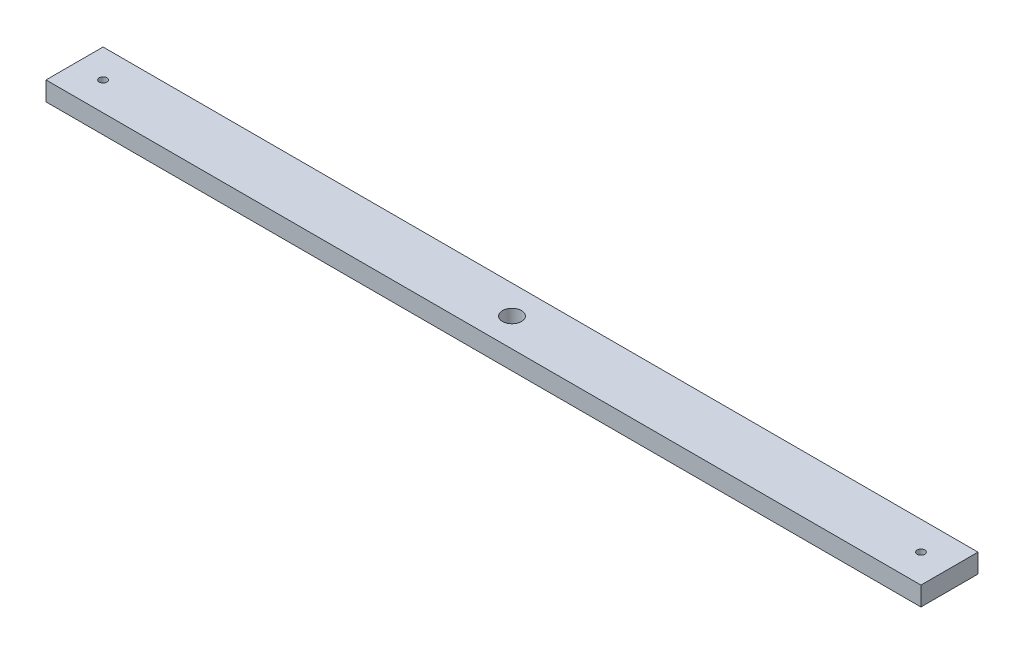
SolidWorks part; units mm, degrees
material "6061 Alloy"
ref_plane "Front Plane" through (0, 0, 0) normal (0, 0, 1) x (1, 0, 0)
ref_plane "Top Plane" through (0, 0, 0) normal (0, 1, 0) x (1, 0, 0)
ref_plane "Right Plane" through (0, 0, 0) normal (1, 0, 0) x (0, 0, -1)
sketch "Sketch1" plane through (0, 0, 0) normal (1, 0, 0) x (0, 0, -1)
  line L1 (-19.05, -6.35) -> (19.05, -6.35)
  line L2 (-19.05, -6.35) -> (-19.05, 6.35)
  line L3 (-19.05, 6.35) -> (19.05, 6.35)
  line L4 (19.05, -6.35) -> (19.05, 6.35)
  line L5 (-19.05, -6.35) -> (19.05, 6.35) construction
  line L6 (-19.05, 6.35) -> (19.05, -6.35) construction
  point P0 (0, 0)
  dimension "D1" = 38.1
  dimension "D2" = 12.7
extrude "Boss-Extrude1" add sketch "Sketch1" along normal mid plane 584.2
sketch "Sketch2" plane through (0, 6.35, 0) normal (0, 1, 0) x (1, 0, 0)
  circle A0 centre (0, 0) radius 6.35
  dimension "D1" = 12.7
extrude "Cut-Extrude1" cut sketch "Sketch2" against normal through all
hole_wizard "1/4-20 Tapped Hole1" positions "Sketch4" profile "Sketch3" tap size "1/4-20" standard "ANSI Inch" end condition through all
sketch "Sketch4" plane through (0, -6.35, 0) normal (0, -1, 0) x (-1, 0, 0)
  line L0 (273.05, 0) -> (292.1, 0) construction
  line L1 (292.1, -19.05) -> (292.1, 19.05) construction
  line L4 (-273.05, 0) -> (-292.1, 0) construction
  line L5 (-292.1, -19.05) -> (-292.1, 19.05) construction
  point P0 (273.05, 0)
  point P2 (-273.05, 0)
  dimension "D1" = 19.05
sketch "Sketch3" plane through (-273.05, -6.35, 0) normal (1, 0, 0) x (0, 0, -1)
  line L0 (0, 0) -> (0, 12.7)
  line L1 (0, 12.7) -> (2.5527, 12.7)
  line L2 (2.5527, 12.7) -> (2.5527, 0)
  line L5 (2.5527, 0) -> (0, 0)
  line L11 (0, -6.35) -> (0, 107.95) construction
  dimension "Thread Major Dia." = 5.1054
  dimension "Thru Tap Drill Depth" = 12.7
